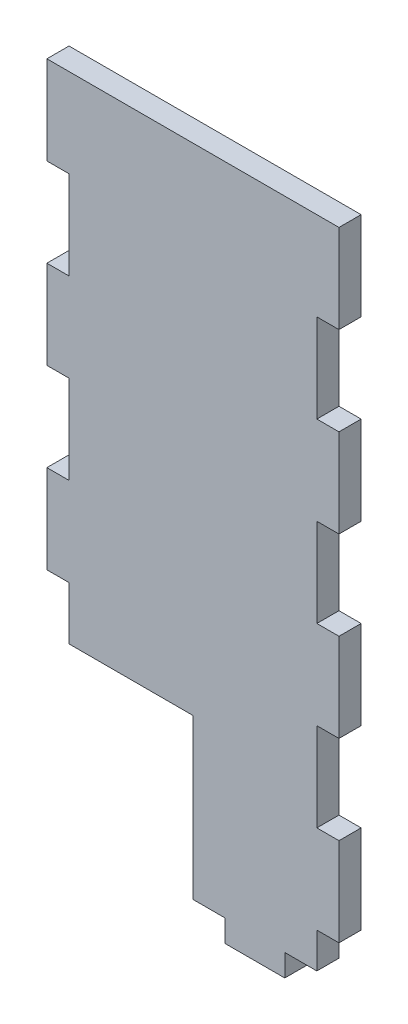
SolidWorks part; units mm, degrees
ref_plane "Front Plane" through (0, 0, 0) normal (0, 0, 1) x (1, 0, 0)
ref_plane "Top Plane" through (0, 0, 0) normal (0, 1, 0) x (1, 0, 0)
ref_plane "Right Plane" through (0, 0, 0) normal (1, 0, 0) x (0, 0, -1)
sketch "Sketch1" plane through (0, 0, 0) normal (0, 0, 1) x (1, 0, 0)
  line L0 (35.56, 45.72) -> (41.91, 45.72)
  line L1 (-35.56, 71.12) -> (35.56, 71.12)
  line L2 (-35.56, 71.12) -> (-35.56, -71.12)
  line L3 (-35.56, -71.12) -> (35.56, -71.12)
  line L4 (35.56, 71.12) -> (35.56, -71.12)
  line L5 (35.56, -71.12) -> (0, -71.12)
  line L6 (35.56, -71.12) -> (35.56, -116.84)
  line L7 (35.56, -116.84) -> (0, -116.84)
  line L8 (0, -71.12) -> (0, -116.84)
  line L9 (9.2075, -116.84) -> (26.3525, -116.84)
  line L10 (9.2075, -116.84) -> (9.2075, -123.19)
  line L11 (9.2075, -123.19) -> (26.3525, -123.19)
  line L12 (26.3525, -116.84) -> (26.3525, -123.19)
  line L13 (35.56, 71.12) -> (41.91, 71.12)
  line L14 (35.56, 71.12) -> (35.56, -116.84)
  line L15 (35.56, -116.84) -> (41.91, -116.84)
  line L16 (41.91, 71.12) -> (41.91, -116.84)
  line L17 (35.56, 20.32) -> (41.91, 20.32)
  line L18 (35.56, -5.08) -> (41.91, -5.08)
  line L19 (35.56, -30.48) -> (41.91, -30.48)
  line L20 (35.56, -55.88) -> (41.91, -55.88)
  line L21 (35.56, -81.28) -> (41.91, -81.28)
  line L22 (35.56, -106.68) -> (41.91, -106.68)
  line L23 (35.56, 71.12) -> (35.56, 45.72) construction
  line L24 (-35.56, 45.72) -> (-41.91, 45.72)
  line L25 (-35.56, 71.12) -> (-41.91, 71.12)
  line L26 (-35.56, 71.12) -> (-35.56, -71.12)
  line L27 (-35.56, -71.12) -> (-41.91, -71.12)
  line L28 (-41.91, 71.12) -> (-41.91, -71.12)
  line L29 (-35.56, 20.32) -> (-41.91, 20.32)
  line L30 (-35.56, -5.08) -> (-41.91, -5.08)
  line L31 (-35.56, -30.48) -> (-41.91, -30.48)
  line L32 (-35.56, -55.88) -> (-41.91, -55.88)
  line L33 (-35.56, 71.12) -> (-35.56, 45.72) construction
  point P4 (0, 71.12)
  point P6 (-35.56, 0)
  point P14 (17.78, -116.84)
  point P15 (17.78, -123.19)
  dimension "D1" = 71.12
  dimension "D2" = 142.24
  dimension "D3" = 187.96
  dimension "D4" = 35.56
  dimension "D5" = 17.145
  dimension "D6" = 6.35
  dimension "D7" = 6.35
  dimension "D9" = 25.4
  dimension "D10" = 6.35
  dimension "D12" = 25.4
  dimension "D8" = 8
  dimension "D11" = 6
extrude "Boss-Extrude1" add sketch "Sketch1" along normal blind 6.35 contours L4 L1 L2 L3 | L3 L8 L7 L6 | L12 L7 L10 L11 | L16 L13 L4 L0 | L14 L18 L16 L17 | L14 L20 L16 L19 | L14 L22 L16 L21 | L32 L26 L31 L28 | L30 L26 L29 L28 | L25 L28 L24 L2
